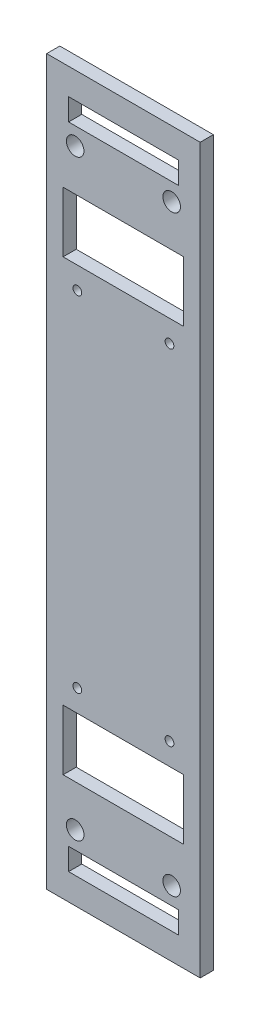
SolidWorks part; units mm, degrees
ref_plane "Plan de face" through (0, 0, 0) normal (0, 0, 1) x (1, 0, 0)
ref_plane "Plan de dessus" through (0, 0, 0) normal (0, 1, 0) x (1, 0, 0)
ref_plane "Plan de droite" through (0, 0, 0) normal (1, 0, 0) x (0, 0, -1)
sketch "Esquisse1" plane through (0, 0, 0) normal (0, 0, 1) x (1, 0, 0)
  line L1 (-35, 165) -> (35, 165)
  line L2 (-35, 165) -> (-35, -165)
  line L3 (-35, -165) -> (35, -165)
  line L4 (35, 165) -> (35, -165)
  line L5 (-35, 165) -> (35, -165) construction
  line L6 (-35, -165) -> (35, 165) construction
  point P0 (0, 0)
  dimension "D1" = 330
  dimension "D2" = 70
extrude "Boss.-Extru.1" add sketch "Esquisse1" along normal blind 6
sketch "Esquisse2" plane through (0, 0, 6) normal (0, 0, 1) x (1, 0, 0)
  line L0 (-35, 0) -> (35, 0) construction
  line L1 (-35, 165) -> (-35, -165) construction
  line L2 (35, -165) -> (35, 165) construction
  line B0 (-27.5, 116) -> (27.5, 116)
  line B1 (-27.5, 116) -> (-27.5, 88.5)
  line B2 (-27.5, 88.5) -> (27.5, 88.5)
  line B3 (27.5, 116) -> (27.5, 88.5)
  line B4 (-25, 153) -> (25, 153)
  line B5 (-25, 153) -> (-25, 143)
  line B6 (-25, 143) -> (25, 143)
  line B7 (25, 153) -> (25, 143)
  circle B8 centre (-21, 78.5) radius 2
  circle B9 centre (21, 78.5) radius 2
  circle B10 centre (-22, 135) radius 4
  circle B11 centre (22, 135) radius 4
  line B12 (-27.5, -116) -> (27.5, -116)
  line B13 (-27.5, -116) -> (-27.5, -88.5)
  line B14 (-27.5, -88.5) -> (27.5, -88.5)
  line B15 (27.5, -116) -> (27.5, -88.5)
  line B16 (-25, -153) -> (25, -153)
  line B17 (-25, -153) -> (-25, -143)
  line B18 (-25, -143) -> (25, -143)
  line B19 (25, -153) -> (25, -143)
  circle B20 centre (-21, -78.5) radius 2
  circle B21 centre (21, -78.5) radius 2
  circle B22 centre (-22, -135) radius 4
  circle B23 centre (22, -135) radius 4
  dimension "D2" = 7.5
  dimension "D1" = 78.5
sketch_block_instance "Bloc3-1"
sketch_block "Bloc3" parameters "D3"=4, "D5"=8, "D1"=55, "D2"=27.5, "D4"=10, "D6"=8, "D7"=10, "D8"=50, "D9"=27
sketch_block_instance "Bloc3-2"
extrude "Enlèv. mat.-Extru.2" cut sketch "Esquisse2" against normal through all
